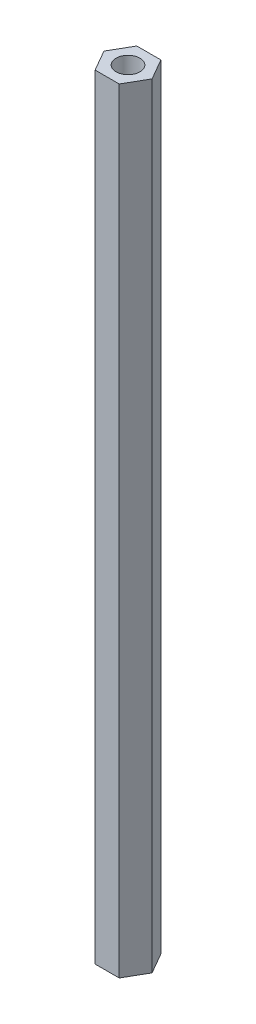
SolidWorks part; units mm, degrees
ref_plane "Front Plane" through (0, 0, 0) normal (0, 0, 1) x (1, 0, 0)
ref_plane "Top Plane" through (0, 0, 0) normal (0, 1, 0) x (1, 0, 0)
ref_plane "Right Plane" through (0, 0, 0) normal (1, 0, 0) x (0, 0, -1)
sketch "Sketch1" plane through (0, 0, 0) normal (0, 1, 0) x (1, 0, 0)
  line L1 (4.0415, 0) -> (2.0207, 3.5)
  line L2 (2.0207, 3.5) -> (-2.0207, 3.5)
  line L3 (-2.0207, 3.5) -> (-4.0415, 0)
  line L4 (-4.0415, 0) -> (-2.0207, -3.5)
  line L5 (-2.0207, -3.5) -> (2.0207, -3.5)
  line L6 (2.0207, -3.5) -> (4.0415, 0)
  circle A0 centre (0, 0) radius 3.5 construction
  circle A1 centre (0, 0) radius 2
  dimension "D1" = 4
  dimension "D2" = 7
extrude "Boss-Extrude1" add sketch "Sketch1" along normal blind 130
